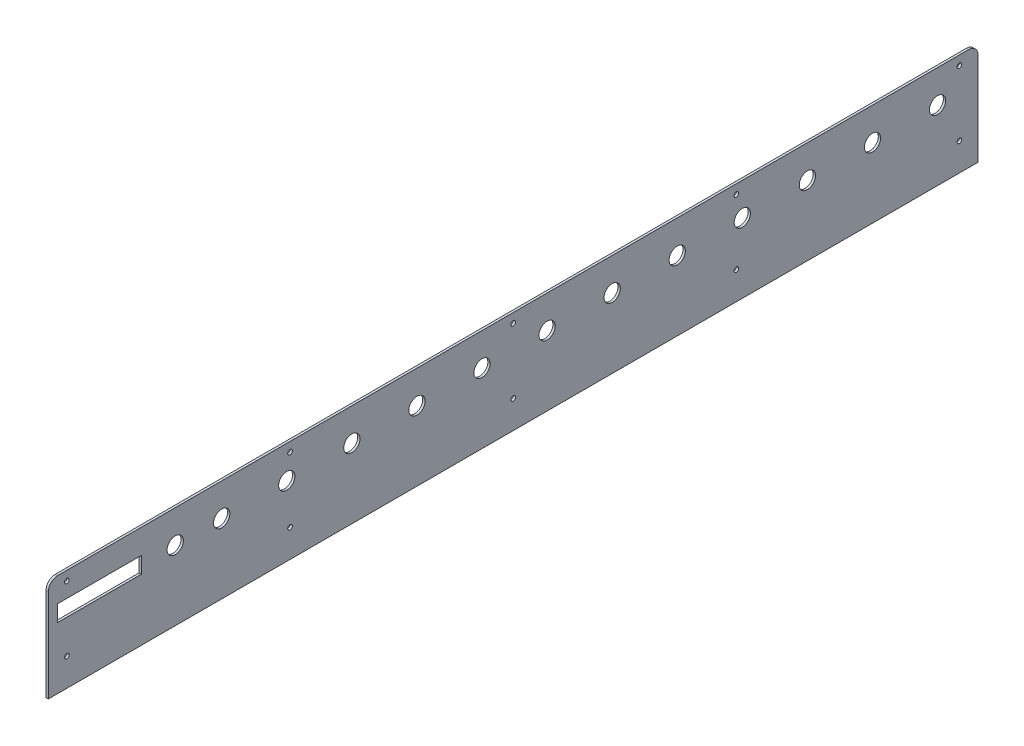
SolidWorks part; units mm, degrees
ref_plane "Front Plane" through (0, 0, 0) normal (0, 0, 1) x (1, 0, 0)
ref_plane "Top Plane" through (0, 0, 0) normal (0, 1, 0) x (1, 0, 0)
ref_plane "Right Plane" through (0, 0, 0) normal (1, 0, 0) x (0, 0, -1)
ref_plane "Plane1" through (2.5, 0, 0) normal (1, 0, 0) x (0, 0, -1)
sketch "Sketch1" plane through (2.5, 0, 0) normal (1, 0, 0) x (0, 0, -1)
  line L0 (1000, 0) -> (1000, 100)
  line L1 (990, 110) -> (10, 110)
  line L2 (0, 100) -> (0, 0)
  line L3 (0, 0) -> (1000, 0)
  line L4 (10, 66.25) -> (10, 83.75)
  line L5 (10, 83.75) -> (100, 83.75)
  line L6 (100, 83.75) -> (100, 66.25)
  line L7 (100, 66.25) -> (10, 66.25)
  arc A0 (1000, 100) -> (990, 110) centre (990, 100) ccw
  arc A1 (10, 110) -> (0, 100) centre (10, 100) ccw
  circle A2 centre (136.5, 75) radius 8.75
  circle A3 centre (186.5, 75) radius 8.75
  circle A4 centre (256.5, 75) radius 8.75
  circle A5 centre (326.5, 75) radius 8.75
  circle A6 centre (396.5, 75) radius 8.75
  circle A7 centre (466.5, 75) radius 8.75
  circle A8 centre (536.5, 75) radius 8.75
  circle A9 centre (606.5, 75) radius 8.75
  circle A10 centre (676.5, 75) radius 8.75
  circle A11 centre (746.5, 75) radius 8.75
  circle A12 centre (816.5, 75) radius 8.75
  circle A13 centre (886.5, 75) radius 8.75
  circle A14 centre (956.5, 75) radius 8.75
extrude "Boss-Extrude1" add sketch "Sketch1" against normal blind 2.5
sketch "Sketch2" plane through (2.5, 0, 0) normal (1, 0, 0) x (0, 0, -1)
  line L0 (990, 110) -> (10, 110) construction
  line L1 (1000, 0) -> (1000, 100) construction
  line L2 (0, 100) -> (0, 0) construction
  line L3 (0, 0) -> (1000, 0) construction
  circle A0 centre (500, 100) radius 2.5
  circle A1 centre (20, 100) radius 2.5
  circle A2 centre (980, 100) radius 2.5
  circle A3 centre (980, 30) radius 2.5
  circle A4 centre (500, 30) radius 2.5
  circle A5 centre (20, 30) radius 2.5
  circle A6 centre (260, 100) radius 2.5
  circle A7 centre (260, 30) radius 2.5
  circle A8 centre (740, 100) radius 2.5
  circle A9 centre (740, 30) radius 2.5
  dimension "D1" = 5
  dimension "D2" = 10
  dimension "D7" = 240
  dimension "D8" = 240
  dimension "D9" = 10
  dimension "D3" = 20
  dimension "D4" = 20
  dimension "D5" = 480
  dimension "D6" = 30
extrude "Cut-Extrude1" cut sketch "Sketch2" against normal through all
